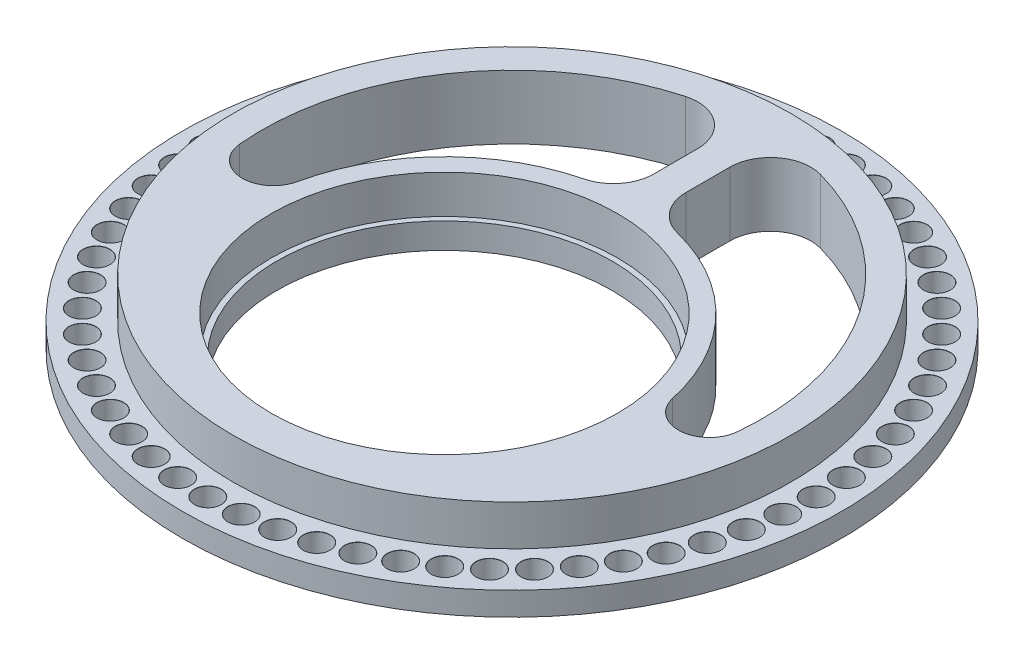
SolidWorks part; units mm, degrees
material "6061-T6 (SS)"
ref_plane "X-Y Datum" through (0, 0, 0) normal (0, 0, 1) x (1, 0, 0)
ref_plane "X-Z Datum" through (0, 0, 0) normal (0, 1, 0) x (1, 0, 0)
ref_plane "Y-Z Datum" through (0, 0, 0) normal (1, 0, 0) x (0, 0, -1)
sketch "Sketch1" plane through (0, 0, 0) normal (0, 1, 0) x (1, 0, 0)
  line L0 (0, 0) -> (0, -12.7) construction
  line L1 (0, -43.0151) -> (0, 43.0151) construction
  line L2 (0, 52.3875) -> (0, 61.9125) construction
  circle A0 centre (0, -12.7) radius 30.988
  circle A1 centre (0, 0) radius 52.3875 construction
  circle A2 centre (0, 0) radius 61.9125
  circle A3 centre (0, 0) radius 57.15 construction
  point P12 (0, 57.15)
  dimension "D2" = 61.976
  dimension "D3" = 104.775
  dimension "D4" = 123.825
  dimension "D5" = 114.3
  dimension "D1" = 12.7
extrude "Slotted-Body Extrude" add sketch "Sketch1" along normal blind 4.191 and the other way blind 0.2032
sketch "Sketch5" plane through (0, 4.191, 0) normal (0, 1, 0) x (1, 0, 0)
  circle A0 centre (0, 0) radius 52.3875 construction
  circle A1 centre (0, 0) radius 52.3875
extrude "Boss-Extrude3" add sketch "Sketch5" along normal blind 7.62
sketch "Sketch6" plane through (0, -0.2032, 0) normal (0, -1, 0) x (1, 0, 0)
  line L0 (0, -79.2756) -> (0, 0) construction
  line L2 (3.014, -37.9067) -> (3.014, -29.6741)
  line L4 (-3.014, -37.9067) -> (-3.014, -29.6741)
  circle A0 centre (0, 12.7) radius 30.988 construction
  circle A1 centre (0, 12.7) radius 30.988 construction
  circle A2 centre (0, 12.7) radius 32.512
  arc A9 (-35.2562, 5.0907) -> (-8.7792, -22.2832) centre (0, 12.7) ccw
  arc A10 (-46.783, 4.406) -> (-12.6921, -45.2435) centre (0, 0) ccw
  arc A11 (-46.783, 4.406) -> (-35.2562, 5.0907) centre (-40.9667, 3.8583) cw
  arc A19 (-3.014, -29.6741) -> (-8.7792, -22.2832) centre (-10.634, -29.6741) ccw
  arc A20 (-3.014, -37.9067) -> (-12.6921, -45.2435) centre (-10.634, -37.9067) cw
  circle A21 centre (0, 0) radius 61.9125 construction
  arc A27 (46.783, 4.406) -> (35.2562, 5.0907) centre (40.9667, 3.8583) ccw
  arc A28 (46.783, 4.406) -> (12.6921, -45.2435) centre (0, 0) cw
  arc A29 (3.014, -37.9067) -> (12.6921, -45.2435) centre (10.634, -37.9067) ccw
  arc A30 (3.014, -29.6741) -> (8.7792, -22.2832) centre (10.634, -29.6741) cw
  arc A31 (35.2562, 5.0907) -> (8.7792, -22.2832) centre (0, 12.7) cw
  point P30 (0, 0)
  point P31 (-3.014, -23.2419)
  point P32 (0, 0)
  point P36 (-3.014, -46.8932)
  dimension "D1" = 65.024
  dimension "D2" = 7.62
  dimension "D3" = 5.842
  dimension "D4" = 46.99
  dimension "D5" = 7.62
  dimension "D6" = 36.068
  dimension "D8" = 8.2326
extrude "Cut-Extrude5" cut sketch "Sketch6" against normal through all
sketch "Sketch8" plane through (0, -0.2032, 0) normal (0, -1, 0) x (1, 0, 0)
  circle A0 centre (0, 12.7) radius 32.512 construction
  circle A1 centre (0, 12.7) radius 32.512
  circle A2 centre (0, 12.7) radius 31.496
  dimension "D1" = 62.992
extrude "Boss-Extrude4" add sketch "Sketch8" against normal blind 4.795 separate body
hole_wizard "Ø5.0mm Dowel Hole2" positions "Sketch9" profile "Sketch10" hole size "Ø5.0" standard "ANSI Metric" end condition through all
sketch "Sketch9" plane through (0, 4.191, 0) normal (0, 1, 0) x (1, 0, 0)
  point P0 (0, 57.15)
sketch "Sketch10" plane through (0, 4.191, -57.15) normal (1, 0, 0) x (0, 0, 1)
  line L0 (0, 0) -> (0, 4.3942)
  line L1 (0, 4.3942) -> (2.5, 4.3942)
  line L2 (2.5, 4.3942) -> (2.5, 0.025)
  line L3 (2.5, 0.025) -> (2.525, 0)
  line L5 (2.525, 0) -> (0, 0)
  line L6 (-2.5, 0.025) -> (-2.525, 0) construction
  line L11 (0, -6.35) -> (0, 107.95) construction
  dimension "Thru Hole Dia." = 5
  dimension "Thru Hole Depth" = 4.3942
  dimension "Near C'Sink Dia." = 5.05
  dimension "Near C'Sink Angle" = 90
pattern_circular "CirPattern1" count 60 over 360 about axis through (0, 0, 0) along (0, 1, 0) of "Ø5.0mm Dowel Hole2"
ref_point "Point1"
ref_plane "Plane1" through (0, 0, 0) normal (1, 0, 0) x (0, 0, -1)
split line "Split Line1" [suppressed]
ref_point "Point2"
ref_point "Point3"
ref_point "Point4"
ref_point "Point5"
split line "Split Line2" [suppressed]
split line "Split Line3" [suppressed]
ref_plane "Plane2" [suppressed] through (-42.4707, 0, 0) normal (-1, 0, 0) x (0, 0, 1)
ref_plane "Plane3" [suppressed] through (55.9011, 0, 0) normal (-1, 0, 0) x (0, 0, 1)
split line "Split Line4" [suppressed]
split line "Split Line5" [suppressed]
sketch "Sketch17" plane through (0, 4.191, 0) normal (0, 1, 0) x (1, 0, 0)
  line L0 (-71.12, 66.6242) -> (71.12, 66.6242) construction
  line L1 (-71.12, -66.6242) -> (71.12, -66.6242) construction
  line L2 (-71.12, -66.6242) -> (-71.12, 66.6242) construction
  line L3 (-71.12, 66.6242) -> (71.12, 66.6242) construction
  line L4 (71.12, -66.6242) -> (71.12, 66.6242) construction
  line L5 (-71.12, -66.6242) -> (71.12, 66.6242) construction
  line L6 (-71.12, 66.6242) -> (-45.1836, 42.3273) construction
  line L7 (-71.12, 88.7603) -> (71.12, 88.7603)
  line L11 (-71.12, 59.8198) -> (-15.9607, 59.8198)
  line L12 (-71.12, 88.7603) -> (71.12, 88.7603)
  line L13 (-71.12, 88.7603) -> (-71.12, -66.6242)
  line L14 (-71.12, -66.6242) -> (71.12, -66.6242)
  line L15 (71.12, 88.7603) -> (71.12, -66.6242)
  line L16 (15.9607, 59.8198) -> (71.12, 59.8198)
  line L17 (0, 0) -> (71.12, -66.6242) construction
  arc A1 (15.9607, 59.8198) -> (-15.9607, 59.8198) centre (0, 0) ccw
  point P0 (0, 0)
  dimension "D1" = 142.24
  dimension "D2" = 133.2484
  dimension "D3" = 22.1361
sketch "Sketch13" plane through (0, 11.811, 0) normal (0, 1, 0) x (1, 0, 0)
  line L0 (3.014, 29.6741) -> (3.014, 37.9067) construction
  line L1 (-3.014, 37.9067) -> (-3.014, 29.6741) construction
  line L2 (3.014, 29.6741) -> (3.014, 37.9067) construction
  line L3 (-3.014, 37.9067) -> (-3.014, 29.6741) construction
  line L4 (-6.062, 37.9067) -> (-6.062, 29.6741)
  line L5 (6.062, 29.6741) -> (6.062, 37.9067)
  circle A0 centre (0, -12.7) radius 31.496 construction
  circle A1 centre (0, -12.7) radius 31.496 construction
  circle A2 centre (0, -12.7) radius 28.448
  arc A3 (35.2562, -5.0907) -> (46.783, -4.406) centre (40.9667, -3.8583) ccw construction
  arc A4 (35.2562, -5.0907) -> (8.7792, 22.2832) centre (0, -12.7) ccw construction
  arc A5 (3.014, 29.6741) -> (8.7792, 22.2832) centre (10.634, 29.6741) ccw construction
  arc A6 (46.783, -4.406) -> (12.6921, 45.2435) centre (0, 0) ccw construction
  arc A7 (12.6921, 45.2435) -> (3.014, 37.9067) centre (10.634, 37.9067) ccw construction
  arc A8 (-46.783, -4.406) -> (-35.2562, -5.0907) centre (-40.9667, -3.8583) ccw construction
  arc A9 (-8.7792, 22.2832) -> (-35.2562, -5.0907) centre (0, -12.7) ccw construction
  arc A10 (-8.7792, 22.2832) -> (-3.014, 29.6741) centre (-10.634, 29.6741) ccw construction
  arc A11 (-3.014, 37.9067) -> (-12.6921, 45.2435) centre (-10.634, 37.9067) ccw construction
  arc A12 (-12.6921, 45.2435) -> (-46.783, -4.406) centre (0, 0) ccw construction
  arc A13 (35.2562, -5.0907) -> (46.783, -4.406) centre (40.9667, -3.8583) ccw construction
  arc A14 (35.2562, -5.0907) -> (8.7792, 22.2832) centre (0, -12.7) ccw construction
  arc A15 (3.014, 29.6741) -> (8.7792, 22.2832) centre (10.634, 29.6741) ccw construction
  arc A16 (46.783, -4.406) -> (12.6921, 45.2435) centre (0, 0) ccw construction
  arc A17 (12.6921, 45.2435) -> (3.014, 37.9067) centre (10.634, 37.9067) ccw construction
  arc A18 (-46.783, -4.406) -> (-35.2562, -5.0907) centre (-40.9667, -3.8583) ccw construction
  arc A19 (-8.7792, 22.2832) -> (-35.2562, -5.0907) centre (0, -12.7) ccw construction
  arc A20 (-8.7792, 22.2832) -> (-3.014, 29.6741) centre (-10.634, 29.6741) ccw construction
  arc A21 (-3.014, 37.9067) -> (-12.6921, 45.2435) centre (-10.634, 37.9067) ccw construction
  arc A22 (-12.6921, 45.2435) -> (-46.783, -4.406) centre (0, 0) ccw construction
  arc A23 (-11.8689, 42.3087) -> (-43.7484, -4.1202) centre (0, 0) ccw
  arc A24 (-43.7484, -4.1202) -> (-38.2356, -4.4477) centre (-40.9667, -3.8583) ccw
  arc A25 (-9.5211, 25.2396) -> (-38.2356, -4.4477) centre (0, -12.7) ccw
  arc A26 (-9.5211, 25.2396) -> (-6.062, 29.6741) centre (-10.634, 29.6741) ccw
  arc A27 (-6.062, 37.9067) -> (-11.8689, 42.3087) centre (-10.634, 37.9067) ccw
  arc A28 (11.8689, 42.3087) -> (6.062, 37.9067) centre (10.634, 37.9067) ccw
  arc A29 (6.062, 29.6741) -> (9.5211, 25.2396) centre (10.634, 29.6741) ccw
  arc A30 (38.2356, -4.4477) -> (9.5211, 25.2396) centre (0, -12.7) ccw
  arc A31 (38.2356, -4.4477) -> (43.7484, -4.1202) centre (40.9667, -3.8583) ccw
  arc A32 (43.7484, -4.1202) -> (11.8689, 42.3087) centre (0, 0) ccw
  dimension "D1" = 3.048
  dimension "D2" = 3.048
sketch "Sketch11" plane through (0, -0.2032, 0) normal (0, -1, 0) x (1, 0, 0)
  line L1 (-61.9125, -61.9125) -> (61.9125, -61.9125)
  line L2 (-61.9125, -61.9125) -> (-61.9125, 61.9125)
  line L3 (-61.9125, 61.9125) -> (61.9125, 61.9125)
  line L4 (61.9125, -61.9125) -> (61.9125, 61.9125)
  line L5 (-61.9125, -61.9125) -> (61.9125, 61.9125) construction
  line L6 (-61.9125, 61.9125) -> (61.9125, -61.9125) construction
  circle A0 centre (0, 0) radius 61.9125 construction
  point P0 (0, 0)
sketch "Sketch14" plane through (0, 4.191, 0) normal (0, 1, 0) x (1, 0, 0)
  line L0 (-61.9125, 61.9125) -> (-61.9125, -61.9125) construction
  line L1 (-61.9125, 61.9125) -> (61.9125, 61.9125) construction
  line L2 (-61.9125, 61.9125) -> (-61.9125, -61.9125) construction
  line L3 (-61.9125, 61.9125) -> (61.9125, 61.9125) construction
  line L7 (-61.9125, -61.9125) -> (61.9125, 61.9125) construction
  line L8 (-61.9125, -61.9125) -> (61.9125, 61.9125)
  line L9 (0, -0.6085) -> (0, 49999.3915) construction
  circle A0 centre (0, 0) radius 61.9125 construction
  circle A2 centre (0, 0) radius 61.9125 construction
  arc A3 (-62.4462, 2.4493) -> (62.4462, 2.4493) centre (0, -0.6085) cw
  arc A4 (-62.4462, 2.4493) -> (-77.6194, 1.8864) centre (-70.0571, 2.822) cw
  arc A5 (0, 61.9125) -> (-3.7531, 76.0115) centre (-4.0041, 68.3957) ccw
  arc A6 (-77.6194, 1.8864) -> (-3.7531, 76.0115) centre (-26.007, 24.3209) cw
  arc A7 (2.4493, -62.4462) -> (1.8864, -77.6194) centre (2.822, -70.0571) ccw
  arc A8 (2.4493, -62.4462) -> (61.9125, 0) centre (-0.6085, 0) ccw
  arc A9 (61.9125, 0) -> (76.0115, -3.7531) centre (68.3957, -4.0041) cw
  arc A10 (1.8864, -77.6194) -> (76.0115, -3.7531) centre (24.3209, -26.007) ccw
  arc A11 (62.4462, 2.4493) -> (77.6194, 1.8864) centre (70.0571, 2.822) ccw
  arc A12 (0, 61.9125) -> (3.7531, 76.0115) centre (4.0041, 68.3957) cw
  arc A13 (77.6194, 1.8864) -> (3.7531, 76.0115) centre (26.007, 24.3209) ccw
  arc A14 (-2.4493, -62.4462) -> (-61.9125, 0) centre (0.6085, 0) cw
  arc A15 (-61.9125, 0) -> (-76.0115, -3.7531) centre (-68.3957, -4.0041) ccw
  arc A16 (-1.8864, -77.6194) -> (-76.0115, -3.7531) centre (-24.3209, -26.007) cw
  arc A17 (-2.4493, -62.4462) -> (-1.8864, -77.6194) centre (-2.822, -70.0571) cw
  point P13 (-61.9125, 0)
  dimension "D1" = 7.62
  dimension "D2" = 7.62
